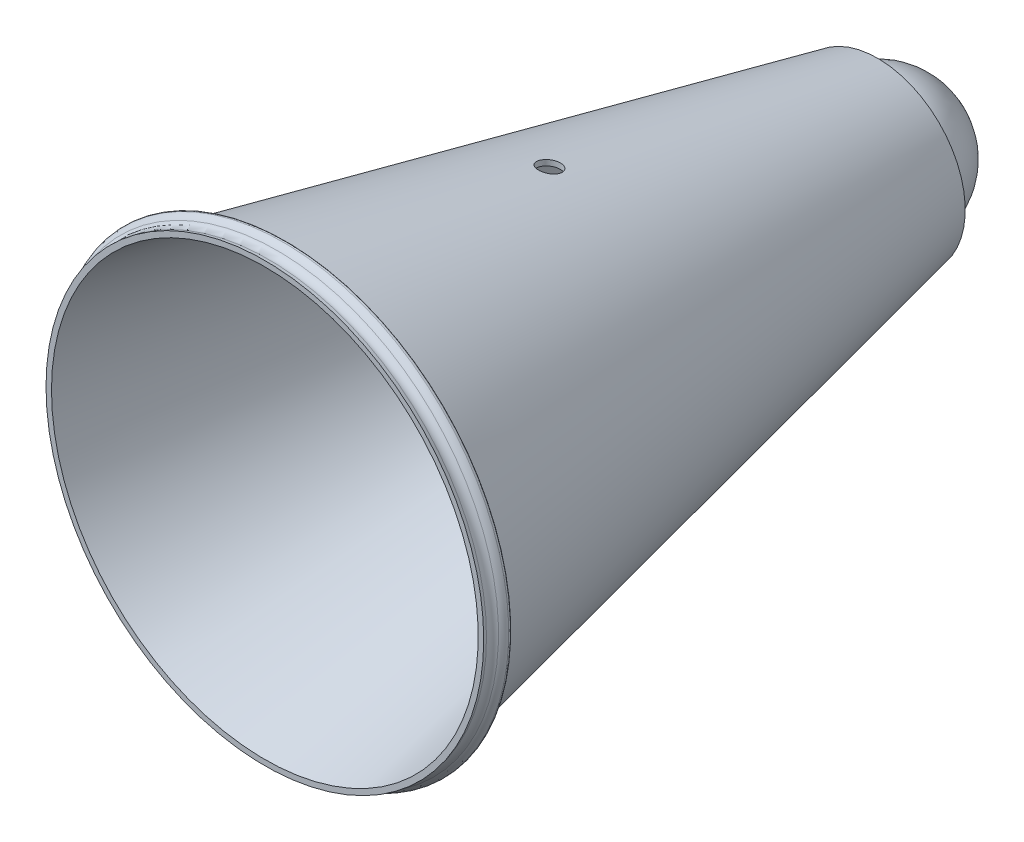
SolidWorks part; units mm, degrees
ref_plane "Front Plane" through (0, 0, 0) normal (0, 0, 1) x (1, 0, 0)
ref_plane "Top Plane" through (0, 0, 0) normal (0, 1, 0) x (1, 0, 0)
ref_plane "Right Plane" through (0, 0, 0) normal (1, 0, 0) x (0, 0, -1)
sketch "Sketch1" plane through (0, 0, 0) normal (1, 0, 0) x (0, 0, -1)
  line L0 (-170.5581, 61.9828) -> (0, 25.4)
  line L1 (55, 0) -> (-55, 0) construction
  line L2 (20.6375, 0) -> (19.05, 0)
  line L3 (0, 55) -> (0, -55) construction
  line L4 (0, 0) -> (-219.4425, 0) construction
  line L5 (-177.8, 63.5) -> (-177.8, 61.9125)
  line L6 (0, 25.4) -> (0, 20.6375)
  line L7 (-177.8, 63.5) -> (-176.7738, 63.2799)
  line L8 (-171.45, 64.6501) -> (-171.45, 63.0863)
  line L9 (-177.8, 61.9125) -> (-12.7, 26.5004)
  line L11 (0, 19.05) -> (-12.7, 19.05)
  line L12 (-12.7, 19.05) -> (-12.7, 26.5004)
  line L13 (-12.7, 26.5004) -> (-12.3671, 28.0526) construction
  arc A0 (0, 19.05) -> (19.05, 0) centre (0, 0) cw
  arc A1 (0, 20.6375) -> (20.6375, 0) centre (0, 0) cw
  arc A2 (-174.2263, 64.2168) -> (-172.4568, 65.4135) centre (-171.5446, 62.1583) cw
  arc A3 (-172.4568, 65.4135) -> (-171.45, 64.6501) centre (-172.2429, 64.6501) cw
  arc A4 (-171.45, 63.0863) -> (-170.5581, 61.9828) centre (-170.3214, 63.0863) ccw
  arc A5 (-176.7738, 63.2799) -> (-174.2263, 64.2168) centre (-176.2411, 65.7634) ccw
  point P11 (0, 31.75)
  dimension "D4" = 38.1
  dimension "D6" = 1.5875
  dimension "D9" = 2.54
  dimension "D10" = 1.1286
  dimension "D8" = 0.7929
  dimension "D1" = 63.5
  dimension "D2" = 12.7
  dimension "D3" = 177.8
  dimension "D5" = 1.5875
  dimension "D7" = 1.5875
  dimension "D11" = 6.35
  dimension "D12" = 50.8
revolve "Revolve1" add sketch "Sketch1" angle 360 about L4
sketch "Sketch2" plane through (0, 0, 0) normal (0, 1, 0) x (1, 0, 0)
  line L0 (0, -49.9409) -> (0, 49.9409) construction
  circle A0 centre (0, -95.25) radius 3.175
  point P7 (0, 0)
  dimension "D1" = 6.35
  dimension "D2" = 95.25
extrude "Cut-Extrude1" cut sketch "Sketch2" against normal through all and the other way through all
